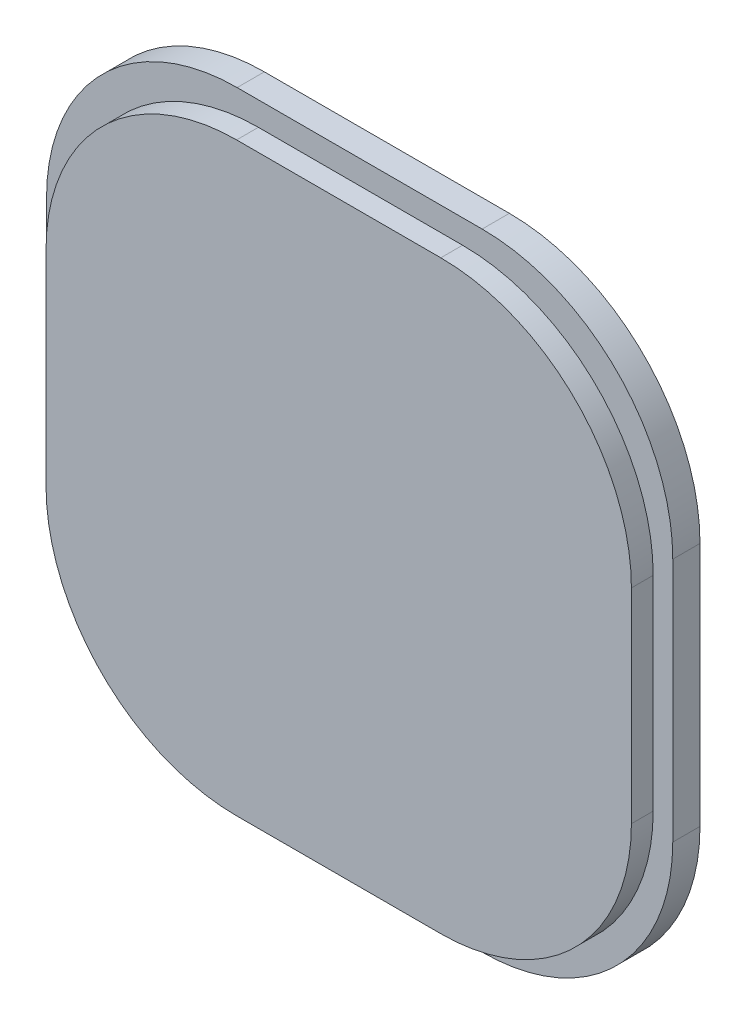
SolidWorks part; units mm, degrees
ref_plane "前视基准面" through (0, 0, 0) normal (0, 0, 1) x (1, 0, 0)
ref_plane "上视基准面" through (0, 0, 0) normal (0, 1, 0) x (1, 0, 0)
ref_plane "右视基准面" through (0, 0, 0) normal (1, 0, 0) x (0, 0, -1)
other "Configuration Table"
sketch "草图1" plane through (0, 0, 0) normal (0, 0, 1) x (1, 0, 0)
  line L1 (-48.6714, 17.3452) -> (-39.6714, 17.3452)
  line L2 (-55.6714, 10.3452) -> (-55.6714, 1.3452)
  line L3 (-48.6714, -5.6548) -> (-39.6714, -5.6548)
  line L4 (-32.6714, 10.3452) -> (-32.6714, 1.3452)
  arc A0 (-55.6714, 1.3452) -> (-48.6714, -5.6548) centre (-48.6714, 1.3452) ccw
  arc A1 (-39.6714, -5.6548) -> (-32.6714, 1.3452) centre (-39.6714, 1.3452) ccw
  arc A2 (-39.6714, 17.3452) -> (-32.6714, 10.3452) centre (-39.6714, 10.3452) cw
  arc A3 (-48.6714, 17.3452) -> (-55.6714, 10.3452) centre (-48.6714, 10.3452) ccw
  point P24 (0, 0)
  dimension "D1" = 7
extrude "凸台-拉伸2" add sketch "草图1" along normal blind 1 contours L2 A0 L3 A1 L4 A2 L1 A3
sketch "草图2" plane through (0, 0, 1) normal (0, 0, 1) x (1, 0, 0)
  line L1 (-47.8906, 16.4711) -> (-40.3906, 16.4711)
  line L2 (-54.8906, 9.4711) -> (-54.8906, 1.9711)
  line L3 (-47.8906, -5.0289) -> (-40.3906, -5.0289)
  line L4 (-33.3906, 9.4711) -> (-33.3906, 1.9711)
  arc A0 (-54.8906, 1.9711) -> (-47.8906, -5.0289) centre (-47.8906, 1.9711) ccw
  arc A1 (-40.3906, -5.0289) -> (-33.3906, 1.9711) centre (-40.3906, 1.9711) ccw
  arc A2 (-40.3906, 16.4711) -> (-33.3906, 9.4711) centre (-40.3906, 9.4711) cw
  arc A3 (-47.8906, 16.4711) -> (-54.8906, 9.4711) centre (-47.8906, 9.4711) ccw
  dimension "D1" = 7
extrude "凸台-拉伸3" add sketch "草图2" along normal blind 0.8 contours L2 A0 L3 A1 L4 A2 L1 A3
